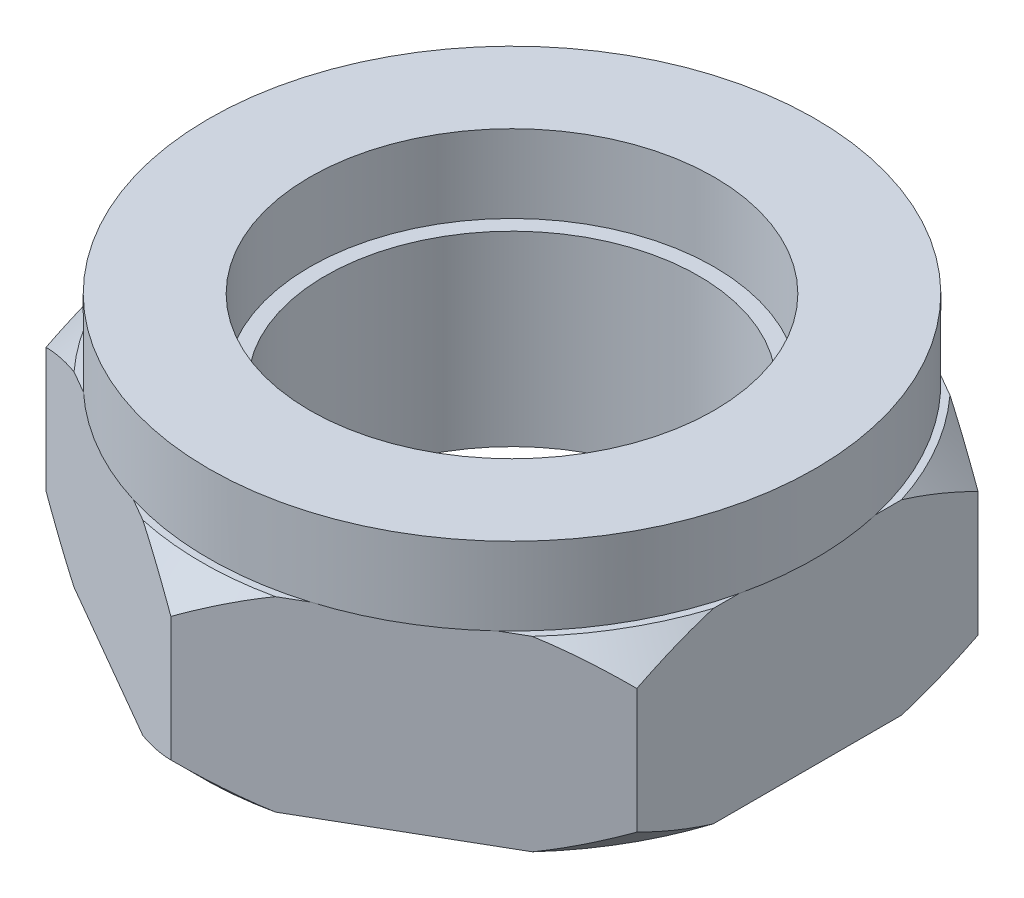
SolidWorks part; units mm, degrees
material "1.0553 (S355J0)"
ref_plane "Płaszczyzna przednia" through (0, 0, 0) normal (0, 0, 1) x (1, 0, 0)
ref_plane "Płaszczyzna górna" through (0, 0, 0) normal (0, 1, 0) x (1, 0, 0)
ref_plane "Płaszczyzna prawa" through (0, 0, 0) normal (1, 0, 0) x (0, 0, -1)
sketch "Szkic1" plane through (0, 0, 0) normal (0, 1, 0) x (1, 0, 0)
  line L1 (9.5, -5.4848) -> (9.5, 5.4848)
  line L2 (9.5, 5.4848) -> (0, 10.9697)
  line L3 (0, 10.9697) -> (-9.5, 5.4848)
  line L4 (-9.5, 5.4848) -> (-9.5, -5.4848)
  line L5 (-9.5, -5.4848) -> (0, -10.9697)
  line L6 (0, -10.9697) -> (9.5, -5.4848)
  circle A0 centre (0, 0) radius 9.5 construction
  circle A1 centre (0, 0) radius 6
  dimension "D1" = 19
  dimension "D2" = 12
extrude "Dodanie-wyciągnięcie1" add sketch "Szkic1" along normal mid plane 6
sketch "Szkic3" plane through (0, 0, 0) normal (1, 0, 0) x (0, 0, -1)
  line L0 (10.9697, 3) -> (10.9697, 2)
  line L1 (10.9697, 3) -> (10.9697, -3) construction
  line L2 (10.9697, 2) -> (9.9697, 3)
  line L3 (5.4848, 3) -> (10.9697, 3) construction
  line L4 (9.9697, 3) -> (10.9697, 3)
  line L5 (0, 0) -> (-12.8095, 0) construction
  line L6 (9.9697, -3) -> (10.9697, -3)
  line L7 (10.9697, -2) -> (9.9697, -3)
  line L8 (10.9697, -3) -> (10.9697, -2)
  line L9 (0, 0) -> (0, 8.5312) construction
  dimension "D1" = 45
  dimension "D2" = 1
revolve "Wycięcie-obrót9" cut sketch "Szkic3" angle 360 about L9
sketch "Szkic4" plane through (0, 3, 0) normal (0, 1, 0) x (1, 0, 0)
  circle A0 centre (0, 0) radius 9.75
  circle A1 centre (0, 0) radius 6.5
  dimension "D1" = 13
  dimension "D2" = 19.5
extrude "Dodanie-wyciągnięcie2" add sketch "Szkic4" along normal blind 2.5
